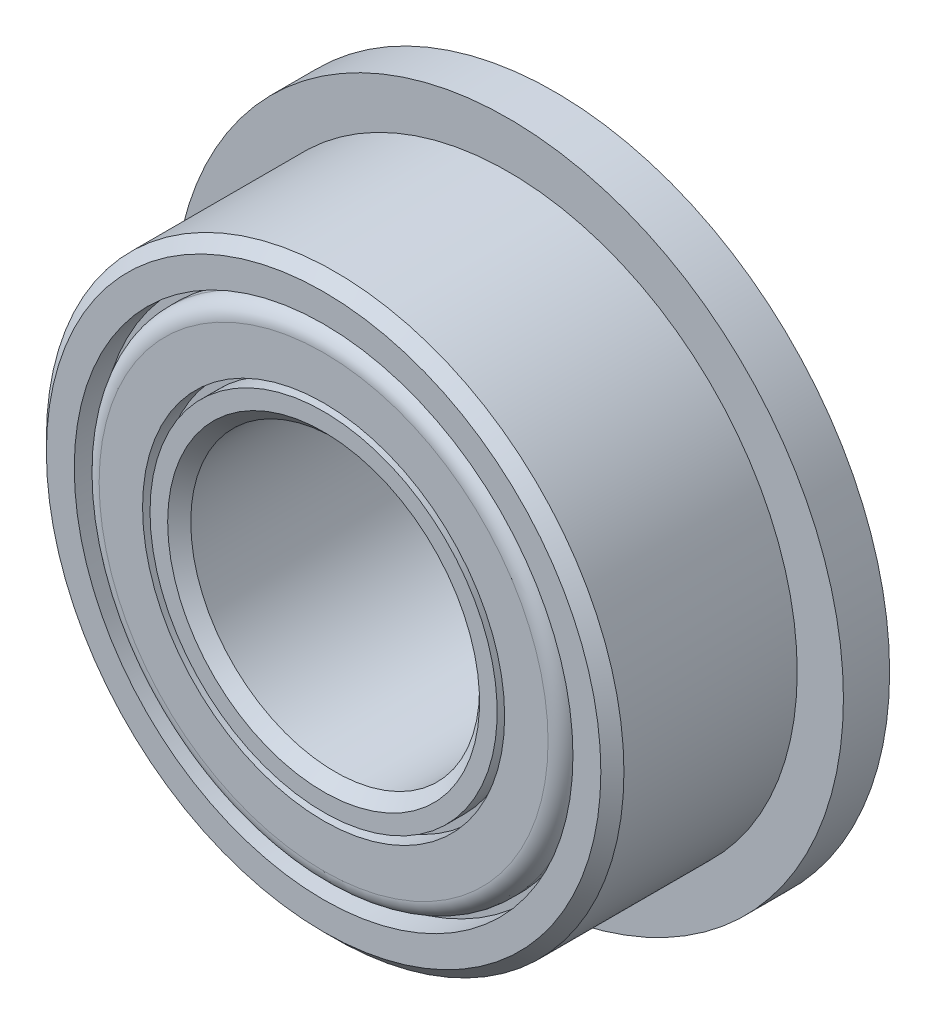
SolidWorks part; units mm, degrees
ref_plane "Front Plane" through (0, 0, 0) normal (0, 0, 1) x (1, 0, 0)
ref_plane "Top Plane" through (0, 0, 0) normal (0, 1, 0) x (1, 0, 0)
ref_plane "Right Plane" through (0, 0, 0) normal (1, 0, 0) x (0, 0, -1)
sketch "Sketch1" plane through (0, 0, 0) normal (1, 0, 0) x (0, 0, -1)
  line L0 (0, 0) -> (3.1741, 0) construction
  line L1 (0, 2.5) -> (0, 0) construction
  line L2 (-2, 2.5) -> (2, 2.5)
  line L3 (-2, 2.5) -> (-2, 5)
  line L4 (1.2, 5.8) -> (2, 5.8)
  line L5 (2, 2.5) -> (2, 5.8)
  line L6 (1.2, 5) -> (-2, 5)
  line L7 (1.2, 5) -> (1.2, 5.8)
  dimension "D1" = 2.5
  dimension "D2" = 5
  dimension "D3" = 4
  dimension "D4" = 0.8
  dimension "D5" = 5.8
revolve "Revolve1" add sketch "Sketch1" angle 360 about L0
chamfer "Chamfer1" distance 0.2 angle 45 3 edges at (2.5, 0, -2) (2.5, 0, 2) (5, 0, 2)
sketch "Sketch2" plane through (0, 0, 0) normal (1, 0, 0) x (0, 0, -1)
  line L0 (-2, 4.3171) -> (-1.5568, 4.3171)
  line L1 (-2, 4.8) -> (-2, -4.8) construction
  line L2 (-1.5568, 4.3171) -> (-1.5568, 4.1861)
  line L3 (-1.5568, 4.1861) -> (-2, 4.1861)
  line L4 (-2, 4.1861) -> (-2, 3.1345)
  line L5 (-2, 3.1345) -> (-1.668, 3.1345)
  line L6 (-1.668, 3.1345) -> (-1.668, 3.0055)
  line L7 (-1.668, 3.0055) -> (-2, 3.0055)
  line L8 (-2, 3.0055) -> (-2, 2.2647)
  line L9 (-2, 2.2647) -> (-2.5521, 2.2647)
  line L10 (-2.5521, 2.2647) -> (-2.5521, 4.3297)
  line L11 (-2.5521, 4.3297) -> (-2, 4.3297)
  line L12 (-2, 4.3297) -> (-2, 4.3171)
  line L13 (2, 0) -> (-2, 0) construction
  line L14 (2, -5.8) -> (2, 5.8) construction
  point P6 (-2, 4.1861)
  point P18 (0, 0)
  point P21 (-2, 4.1861)
  point P22 (-2, 4.1732)
revolve "Cut-Revolve1" cut sketch "Sketch2" angle 360 about L13
mirror "Mirror3" about plane through (0, 0, 0) normal (0, 0, 1) of "Cut-Revolve1"
fillet "Fillet1" radius 0.3 2 edges at (-4.1861, 0, 2) (-4.1861, 0, -2)
